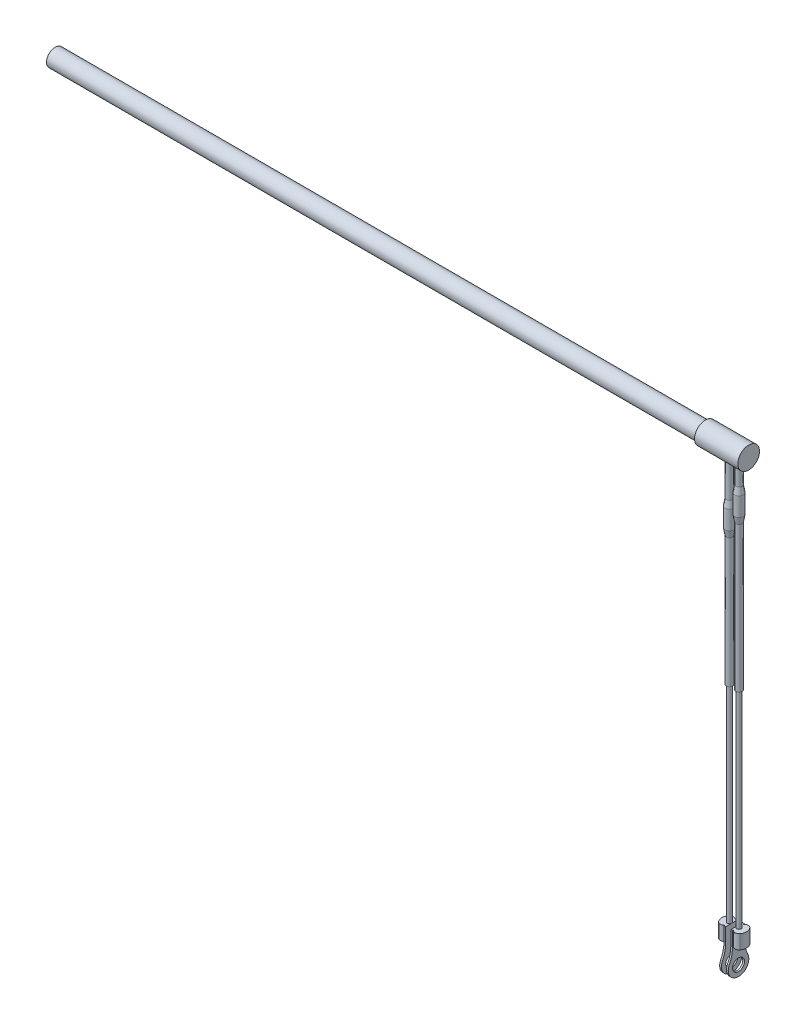
SolidWorks part; units mm, degrees
ref_plane "Front" through (0, 0, 0) normal (0, 0, 1) x (1, 0, 0)
ref_plane "Top" through (0, 0, 0) normal (0, 1, 0) x (1, 0, 0)
ref_plane "Right" through (0, 0, 0) normal (1, 0, 0) x (0, 0, -1)
ref_plane "Plane1" through (0, 0, 0) normal (0, 0, 1) x (1, 0, 0)
sketch "Sketch1" plane through (0, 0, 0) normal (0, 0, 1) x (1, 0, 0)
  line L0 (-313.3333, 0) -> (-313.3333, 4)
  line L1 (-313.3333, 4) -> (-13.3333, 4)
  line L2 (-13.3333, 4) -> (-13.3333, 5)
  line L3 (-13.3333, 5) -> (6.6667, 5)
  line L4 (6.6667, 5) -> (6.6667, 0)
  line L5 (6.6667, 0) -> (-313.3333, 0)
  line L6 (6.6667, 0) -> (-313.3333, 0) construction
revolve "Revolve1" add sketch "Sketch1" angle 360 about L6
ref_plane "Plane2" through (0, 0, 0) normal (0, 0, 1) x (1, 0, 0)
sketch "Sketch2" plane through (0, 0, 0) normal (0, 0, 1) x (1, 0, 0)
  line L0 (2.2, -4) -> (3.64, -4)
  line L1 (3.64, -4) -> (3.64, -13)
  line L2 (3.64, -13) -> (4.2, -16.1759)
  line L3 (4.2, -16.1759) -> (4.2, -24.8241)
  line L4 (4.2, -24.8241) -> (3.64, -28)
  line L5 (3.64, -28) -> (3.64, -95)
  line L6 (3.64, -95) -> (3.24, -95)
  line L7 (3.24, -95) -> (3.24, -195)
  line L8 (3.24, -195) -> (2.2, -195)
  line L9 (2.2, -195) -> (2.2, -4)
  line L10 (2.2, -195) -> (2.2, -4) construction
revolve "Revolve2" add sketch "Sketch2" angle 360 about L10
ref_plane "Plane3" through (0, 0, 0) normal (0, 0, 1) x (1, 0, 0)
sketch "Sketch3" plane through (0, 0, 0) normal (0, 0, 1) x (1, 0, 0)
  line L0 (-2.2, -195) -> (-3.24, -195)
  line L1 (-3.24, -195) -> (-3.24, -95)
  line L2 (-3.24, -95) -> (-3.64, -95)
  line L3 (-3.64, -95) -> (-3.64, -35.5)
  line L4 (-3.64, -35.5) -> (-4.2, -32.3241)
  line L5 (-4.2, -32.3241) -> (-4.2, -23.6759)
  line L6 (-4.2, -23.6759) -> (-3.64, -20.5)
  line L7 (-3.64, -20.5) -> (-3.64, -4)
  line L8 (-3.64, -4) -> (-2.2, -4)
  line L9 (-2.2, -4) -> (-2.2, -195)
  line L10 (-2.2, -4) -> (-2.2, -195) construction
revolve "Revolve3" add sketch "Sketch3" angle 360 about L10
ref_plane "Plane4" through (0, -190, 0) normal (0, 1, 0) x (-1, 0, 0)
sketch "Sketch4" plane through (0, -190, 0) normal (0, 1, 0) x (-1, 0, 0)
  circle A0 centre (0, 0) radius 25.8174
extrude "Cut-Extrude1" cut sketch "Sketch4" against normal blind 20
ref_plane "Plane5" through (0, -190, 0) normal (0, 1, 0) x (-1, 0, 0)
sketch "Sketch5" plane through (0, -190, 0) normal (0, 1, 0) x (-1, 0, 0)
  arc A0 (-1.93, -2.25) -> (-1.93, 2.25) centre (-4.93, 0) ccw
  arc A1 (-1.93, 2.25) -> (-4.93, 2.25) centre (-3.43, 1.125) ccw
  arc A2 (-4.93, 2.25) -> (-4.93, -2.25) centre (-1.93, 0) ccw
  arc A3 (-4.93, -2.25) -> (-1.93, -2.25) centre (-3.43, -1.125) ccw
extrude "Boss-Extrude2" add sketch "Sketch5" against normal blind 6.5
ref_plane "Plane6" through (0, -190, 0) normal (0, 1, 0) x (-1, 0, 0)
sketch "Sketch6" plane through (0, -190, 0) normal (0, 1, 0) x (-1, 0, 0)
  arc A0 (4.93, -2.25) -> (4.93, 2.25) centre (1.93, 0) ccw
  arc A1 (4.93, 2.25) -> (1.93, 2.25) centre (3.43, 1.125) ccw
  arc A2 (1.93, 2.25) -> (1.93, -2.25) centre (4.93, 0) ccw
  arc A3 (1.93, -2.25) -> (4.93, -2.25) centre (3.43, -1.125) ccw
extrude "Boss-Extrude3" add sketch "Sketch6" against normal blind 6.5
ref_plane "Plane7" through (1.18, 0, 0) normal (1, 0, 0) x (0, 0, -1)
sketch "Sketch7" plane through (1.18, 0, 0) normal (1, 0, 0) x (0, 0, -1)
  line L0 (2.75, -196.3397) -> (2.75, -190)
  line L1 (2.75, -190) -> (-2.75, -190)
  line L2 (-2.75, -190) -> (-2.75, -196.3397)
  arc A0 (-4.269, -202.9172) -> (4.269, -202.9172) centre (0, -205) ccw
  arc A1 (4.269, -202.9172) -> (2.75, -196.3397) centre (17.75, -196.3397) cw
  arc A2 (-2.75, -196.3397) -> (-4.269, -202.9172) centre (-17.75, -196.3397) cw
  circle A3 centre (0, -205) radius 2.75
extrude "Boss-Extrude4" add sketch "Sketch7" along normal blind 0.8
ref_plane "Plane8" through (-1.18, 0, 0) normal (1, 0, 0) x (0, 0, -1)
sketch "Sketch8" plane through (-1.18, 0, 0) normal (1, 0, 0) x (0, 0, -1)
  line L0 (2.75, -196.3397) -> (2.75, -190)
  line L1 (2.75, -190) -> (-2.75, -190)
  line L2 (-2.75, -190) -> (-2.75, -196.3397)
  arc A0 (-4.269, -202.9172) -> (4.269, -202.9172) centre (0, -205) ccw
  arc A1 (4.269, -202.9172) -> (2.75, -196.3397) centre (17.75, -196.3397) cw
  arc A2 (-2.75, -196.3397) -> (-4.269, -202.9172) centre (-17.75, -196.3397) cw
  circle A3 centre (0, -205) radius 2.75
extrude "Boss-Extrude5" add sketch "Sketch8" against normal blind 0.8
